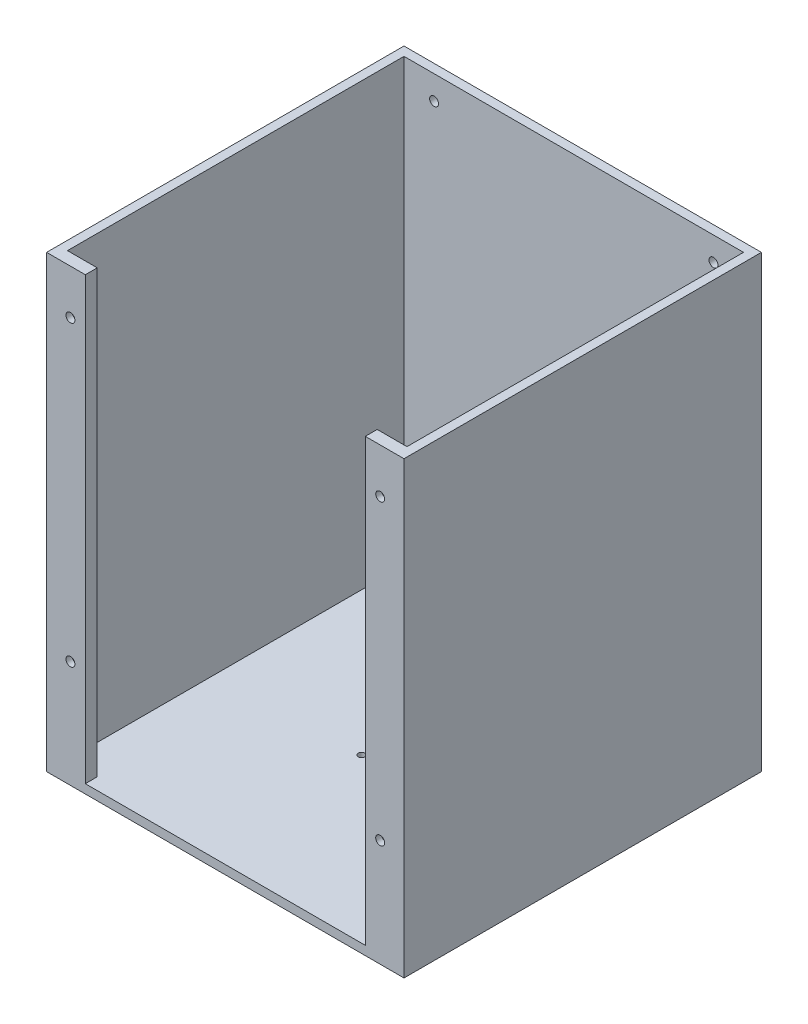
SolidWorks part; units mm, degrees
other "Markup1"
sketch "Sketch8" plane through (60, 0, -60) normal (0.7052, -0.7014, -0.1039) x (0.274, 0.4048, -0.8724)
other "Markup2"
sketch "Sketch9" plane through (60, 0, -60) normal (0.9922, -0.0018, -0.1244) x (-0.0942, 0.6423, -0.7606)
ref_plane "Front Plane" through (0, 0, 0) normal (0, 0, 1) x (1, 0, 0)
ref_plane "Top Plane" through (0, 0, 0) normal (0, 1, 0) x (1, 0, 0)
ref_plane "Right Plane" through (0, 0, 0) normal (1, 0, 0) x (0, 0, -1)
sketch "Sketch1" plane through (0, 0, 0) normal (0, 1, 0) x (1, 0, 0)
  line L5 (-60, 60) -> (60, 60)
  line L6 (-60, 60) -> (-60, -60)
  line L7 (-60, -60) -> (60, -60)
  line L8 (60, 60) -> (60, -60)
  dimension "D1" = 120
  dimension "D2" = 120
  dimension "D3" = 60
  dimension "D4" = 60
extrude "Main-Body" add sketch "Sketch1" along normal blind 151
sketch "Sketch11" plane through (0, 151, 0) normal (0, 1, 0) x (1, 0, 0)
  line L1 (57, -60) -> (-57, -60)
  line L5 (60, 60) -> (-60, 60) construction
  line L6 (-57, -60) -> (57, -60)
  line L14 (-57, -60) -> (-57, 57)
  line L15 (-57, 57) -> (57, 57)
  line L16 (57, -60) -> (57, 57)
  point P0 (0, -1)
  dimension "D1" = 58
  dimension "D2" = 3
  dimension "D3" = 117
  dimension "D4" = 57
  dimension "D5" = 57
extrude "Hollow" cut sketch "Sketch11" against normal blind 148 contours L14 L6 L16 L15
sketch "Sketch12" plane through (57, 0, 0) normal (-1, 0, 0) x (0, 0, 1)
  line L1 (56, 151) -> (60, 151)
  line L2 (56, 151) -> (56, 3)
  line L3 (56, 3) -> (60, 3)
  line L4 (60, 151) -> (60, 3)
  dimension "D1" = 4
extrude "Boss-Extrude1" add sketch "Sketch12" along normal blind 10
sketch "Sketch13" plane through (-57, 0, 0) normal (1, 0, 0) x (0, 0, -1)
  line L1 (-60, 151) -> (-56, 151)
  line L2 (-60, 151) -> (-60, 3)
  line L3 (-60, 3) -> (-56, 3)
  line L4 (-56, 151) -> (-56, 3)
  dimension "D1" = 4
extrude "Boss-Extrude2" add sketch "Sketch13" along normal blind 10
sketch "Sketch14" plane through (0, 0, 0) normal (0, -1, 0) x (0, 0, 1)
  line L0 (-60, -60) -> (-60, 60) construction
  circle A0 centre (-2.225, 9) radius 1.1
  circle A1 centre (5.275, 9) radius 1.1
  circle A2 centre (5.275, -9) radius 1.1
  circle A3 centre (-2.225, -9) radius 1.1
  point P7 (-60, 0)
  dimension "D1" = 2.2
  dimension "D2" = 57.775
  dimension "D3" = 9
  dimension "D4" = 2
  dimension "D5" = 2
extrude "LED-Mounting-Holes" cut sketch "Sketch14" against normal up to next
sketch "Sketch15" plane through (0, 3, 0) normal (0, 1, 0) x (1, 0, 0)
  circle A0 centre (0, -0.05) radius 1.5
  circle A1 centre (-9, 2.225) radius 1.1 construction
  dimension "D1" = 9
  dimension "D3" = 3
  dimension "D2" = 2.275
extrude "LED-Position" cut sketch "Sketch15" against normal blind 1
sketch "Sketch16" plane through (0, 0, -60) normal (0, 0, -1) x (-1, 0, 0)
  circle A0 centre (-46.9, 143) radius 1.5
  dimension "D1" = 13.1
  dimension "D2" = 8
extrude "Bolt-Hole-1" cut sketch "Sketch16" against normal up to next
pattern_linear "LPattern1" count 2 spacing 93.8 along (-1, 0, 0) of "Bolt-Hole-1"
sketch "Sketch18" plane through (0, 0, 56) normal (0, 0, -1) x (-1, 0, 0)
  line L1 (55.2, 136) -> (53.6, 138.7713)
  line L2 (53.6, 138.7713) -> (50.4, 138.7713)
  line L3 (50.4, 138.7713) -> (48.8, 136)
  line L4 (48.8, 136) -> (50.4, 133.2287)
  line L5 (50.4, 133.2287) -> (53.6, 133.2287)
  line L6 (53.6, 133.2287) -> (55.2, 136)
  circle A0 centre (52, 136) radius 3.2 construction
  point P1 (0, 0)
  point P9 (0, 0)
  dimension "D1" = 15
  dimension "D2" = 5
extrude "Cut-Extrude5" cut sketch "Sketch18" against normal blind 2
sketch "Sketch20" plane through (0, 0, 58) normal (0, 0, -1) x (-1, 0, 0)
  circle A0 centre (52, 136) radius 1.5
  point P2 (0, 0)
  point P3 (0, 0)
  point P4 (0, 0)
  point P5 (0, 0)
extrude "Cut-Extrude6" cut sketch "Sketch20" against normal blind 10
sketch "Sketch21" plane through (0, 0, 56) normal (0, 0, -1) x (-1, 0, 0)
  circle A0 centre (52, 36) radius 1.5
  point P2 (0, 0)
extrude "Bolt-Hole1" cut sketch "Sketch21" against normal blind 10
sketch "Sketch28" plane through (0, 0, 56) normal (0, 0, -1) x (-1, 0, 0)
  line L1 (54.9529, 34.7669) -> (54.5443, 37.9407)
  line L2 (54.5443, 37.9407) -> (51.5914, 39.1738)
  line L3 (51.5914, 39.1738) -> (49.0471, 37.2331)
  line L4 (49.0471, 37.2331) -> (49.4557, 34.0593)
  line L5 (49.4557, 34.0593) -> (52.4086, 32.8262)
  line L6 (52.4086, 32.8262) -> (54.9529, 34.7669)
  circle A0 centre (52, 36) radius 3.2 construction
sketch "Sketch29" plane through (0, 0, 56) normal (0, 0, -1) x (-1, 0, 0)
  line L1 (55.2, 36) -> (53.6, 38.7713)
  line L2 (53.6, 38.7713) -> (50.4, 38.7713)
  line L3 (50.4, 38.7713) -> (48.8, 36)
  line L4 (48.8, 36) -> (50.4, 33.2287)
  line L5 (50.4, 33.2287) -> (53.6, 33.2287)
  line L6 (53.6, 33.2287) -> (55.2, 36)
  circle A0 centre (52, 36) radius 3.2 construction
  point P1 (0, 0)
extrude "Nut-hole1" cut sketch "Sketch29" against normal blind 2
sketch "Sketch31" plane through (0, 0, 56) normal (0, 0, -1) x (-1, 0, 0)
  line L0 (-60, 151) -> (60, 151) construction
  circle A0 centre (-52, 136) radius 1.5
  dimension "D1" = 15
sketch "Sketch32" plane through (0, 0, 56) normal (0, 0, -1) x (-1, 0, 0)
  line L1 (-48.8, 136) -> (-50.4, 138.7713)
  line L2 (-50.4, 138.7713) -> (-53.6, 138.7713)
  line L3 (-53.6, 138.7713) -> (-55.2, 136)
  line L4 (-55.2, 136) -> (-53.6, 133.2287)
  line L5 (-53.6, 133.2287) -> (-50.4, 133.2287)
  line L6 (-50.4, 133.2287) -> (-48.8, 136)
  circle A0 centre (-52, 136) radius 3.2 construction
extrude "Nut-Hole3" cut sketch "Sketch32" against normal blind 2
sketch "Sketch33" plane through (0, 0, 56) normal (0, 0, -1) x (-1, 0, 0)
  circle A0 centre (-52, 136) radius 1.5
extrude "Bolt-Hole3" cut sketch "Sketch33" against normal blind 12
sketch "Sketch34" plane through (0, 0, 56) normal (0, 0, -1) x (-1, 0, 0)
  line L1 (-48.8, 36) -> (-50.4, 38.7713)
  line L2 (-50.4, 38.7713) -> (-53.6, 38.7713)
  line L3 (-53.6, 38.7713) -> (-55.2, 36)
  line L4 (-55.2, 36) -> (-53.6, 33.2287)
  line L5 (-53.6, 33.2287) -> (-50.4, 33.2287)
  line L6 (-50.4, 33.2287) -> (-48.8, 36)
  circle A0 centre (-52, 36) radius 3.2 construction
  point P1 (0, 0)
extrude "Nut-hole4" cut sketch "Sketch34" against normal blind 2
sketch "Sketch35" plane through (0, 0, 56) normal (0, 0, -1) x (-1, 0, 0)
  circle A0 centre (-52, 36) radius 1.5
extrude "Cut-Extrude16" cut sketch "Sketch35" against normal blind 12
